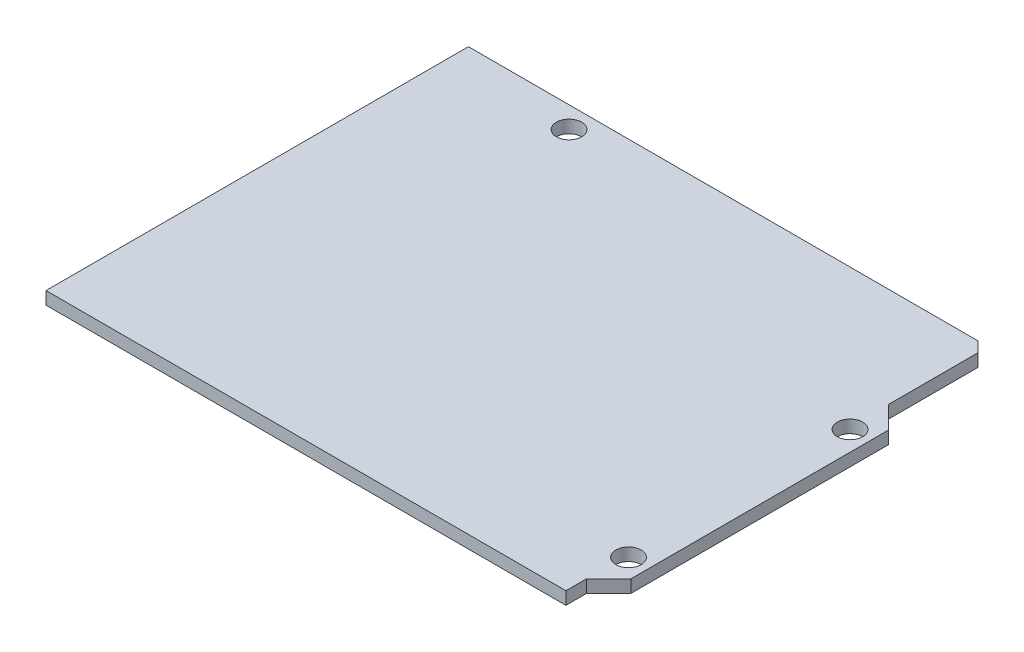
SolidWorks part; units mm, degrees
ref_plane "Front Plane" through (0, 0, 0) normal (0, 0, 1) x (1, 0, 0)
ref_plane "Top Plane" through (0, 0, 0) normal (0, 1, 0) x (1, 0, 0)
ref_plane "Right Plane" through (0, 0, 0) normal (1, 0, 0) x (0, 0, -1)
sketch "Sketch1" plane through (0, 0, 0) normal (0, 1, 0) x (1, 0, 0)
  line L0 (65.6, 0) -> (65.6, 2.6)
  line L1 (0, 0) -> (65.6, 0)
  line L2 (0, 0) -> (0, 53.3)
  line L3 (0, 53.3) -> (64.3, 53.3)
  line L4 (68.4, 5.4) -> (68.4, 37.9)
  line L5 (65.6, 2.6) -> (68.4, 5.4)
  line L6 (68.4, 37.9) -> (65.6, 40.7)
  line L7 (65.6, 40.7) -> (65.6, 52)
  line L8 (65.6, 52) -> (64.3, 53.3)
  circle A0 centre (65.9, 7.6) radius 1.6
  circle A1 centre (65.9, 35.55) radius 1.6
  circle A4 centre (15.4, 50.6) radius 1.6
  dimension "D10" = 3.2
  dimension "D11" = 6
  dimension "D13" = 24.75
  dimension "D1" = 68.4
  dimension "D2" = 53.3
  dimension "D3" = 135
  dimension "D4" = 135
  dimension "D5" = 135
  dimension "D6" = 1.3
  dimension "D7" = 11.3
  dimension "D8" = 2.8
  dimension "D9" = 2.6
  dimension "D12" = 0.9
  dimension "D18" = 1.1
  dimension "D20" = 13.8
extrude "Boss-Extrude1" add sketch "Sketch1" along normal blind 1.6
